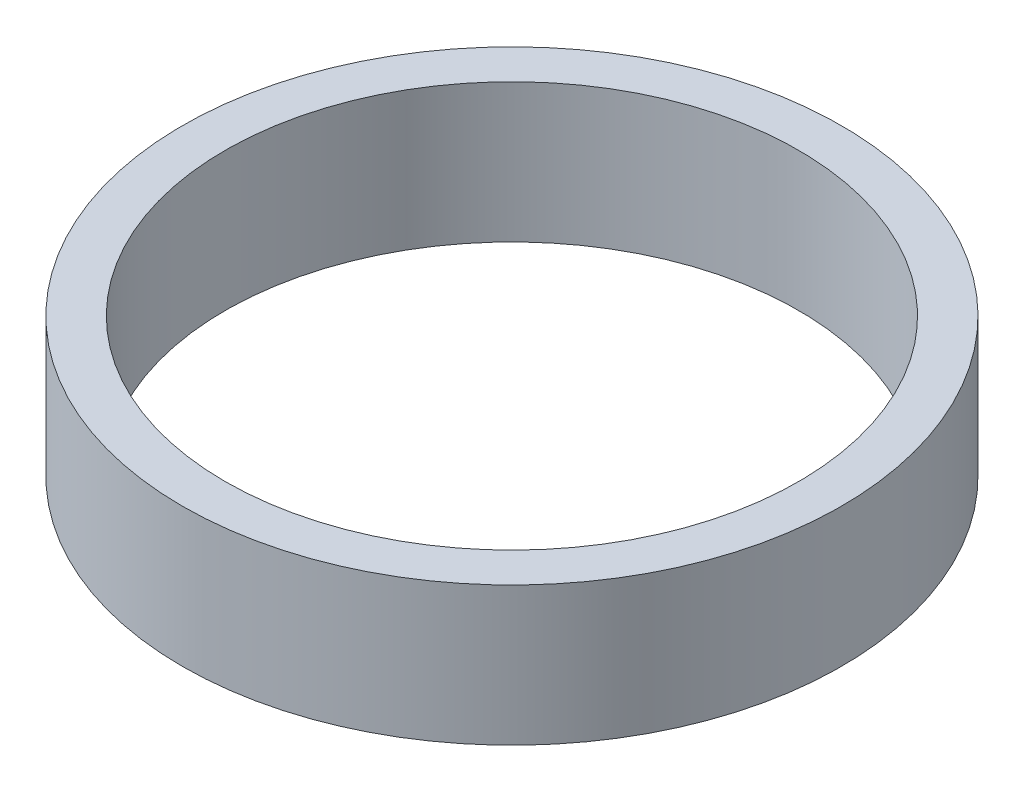
SolidWorks part; units mm, degrees
ref_plane "Front Plane" through (0, 0, 0) normal (0, 0, 1) x (1, 0, 0)
ref_plane "Top Plane" through (0, 0, 0) normal (0, 1, 0) x (1, 0, 0)
ref_plane "Right Plane" through (0, 0, 0) normal (1, 0, 0) x (0, 0, -1)
sketch "Sketch1" plane through (0, 0, 0) normal (0, 1, 0) x (1, 0, 0)
  circle A0 centre (0, 0) radius 30.1625
  circle A1 centre (0, 0) radius 26.2509
  dimension "D1" = 60.325
  dimension "D2" = 52.5018
extrude "Boss-Extrude1" add sketch "Sketch1" along normal blind 12.7
sketch "Sketch3" plane through (0, 0, 0) normal (1, 0, 0) x (0, 0, -1)
  line L0 (-26.2509, 12.7) -> (-26.2509, 0) construction
  line L1 (-26.2509, 12.7) -> (-26.2509, 0) construction
